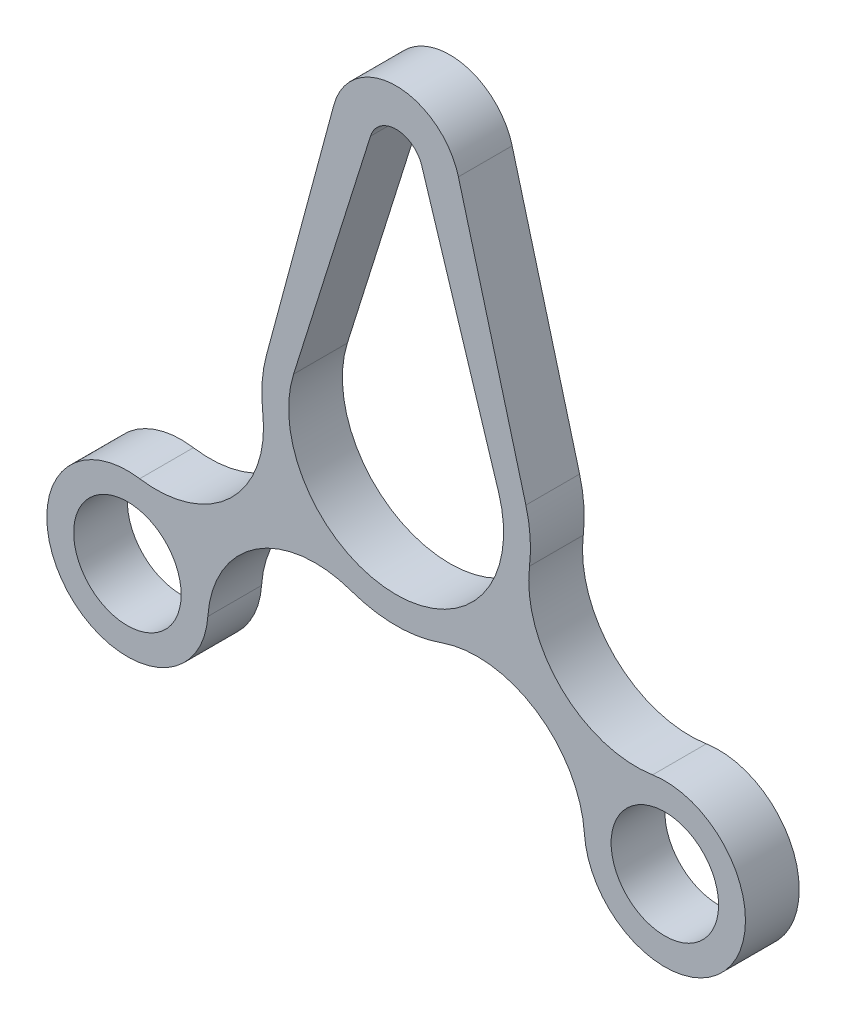
SolidWorks part; units mm, degrees
ref_plane "Front Plane" through (0, 0, 0) normal (0, 0, 1) x (1, 0, 0)
ref_plane "Top Plane" through (0, 0, 0) normal (0, 1, 0) x (1, 0, 0)
ref_plane "Right Plane" through (0, 0, 0) normal (1, 0, 0) x (0, 0, -1)
sketch "Sketch1" plane through (0, 0, 0) normal (0, 0, 1) x (1, 0, 0)
  line L0 (0, 0) -> (50000, 0) construction
  line L1 (0, 0) -> (0, 50000) construction
  line L2 (-24.1402, 6.5) -> (-11.5873, 53.12)
  line L3 (-19.0788, 6) -> (-4.7697, 51.5)
  line L4 (19.0788, 6) -> (4.7697, 51.5)
  line L5 (24.1402, 6.5) -> (11.5873, 53.12)
  arc A0 (-24.1402, 6.5) -> (-24.8188, -3.0042) centre (0, 0) ccw
  arc A1 (-19.0788, 6) -> (19.0788, 6) centre (0, 0) ccw
  circle A2 centre (-50, -40) radius 15
  circle A3 centre (-50, -40) radius 10
  arc A4 (-35.0352, -41.0274) -> (-8.379, -23.554) centre (-15.0822, -42.3973) cw
  arc A5 (-47.7174, -25.1747) -> (-24.8188, -3.0042) centre (-44.6739, -5.4076) ccw
  arc A6 (35.0352, -41.0274) -> (8.379, -23.554) centre (15.0822, -42.3973) ccw
  arc A7 (47.7174, -25.1747) -> (24.8188, -3.0042) centre (44.6739, -5.4076) cw
  circle A8 centre (50, -40) radius 10
  circle A9 centre (50, -40) radius 15
  arc A10 (4.7697, 51.5) -> (-4.7697, 51.5) centre (0, 50) ccw
  arc A11 (11.5873, 53.12) -> (-11.5873, 53.12) centre (0, 50) ccw
  arc A12 (-8.379, -23.554) -> (8.379, -23.554) centre (0, 0) ccw
  arc A13 (24.8188, -3.0042) -> (24.1402, 6.5) centre (0, 0) ccw
  dimension "D1" = 50
  dimension "D2" = 40
  dimension "D3" = 30
  dimension "D4" = 20
  dimension "D7" = 20
  dimension "D8" = 10
  dimension "D9" = 24
  dimension "D5" = 50
  dimension "D6" = 40
  dimension "D10" = 50
extrude "Boss-Extrude1" add sketch "Sketch1" along normal blind 10 contours A7 A13 L5 A11 L2 A0 A5 A2 A4 A12 A6 A9 A10 L4 A1 L3 | A2 A3 | A9 A8
